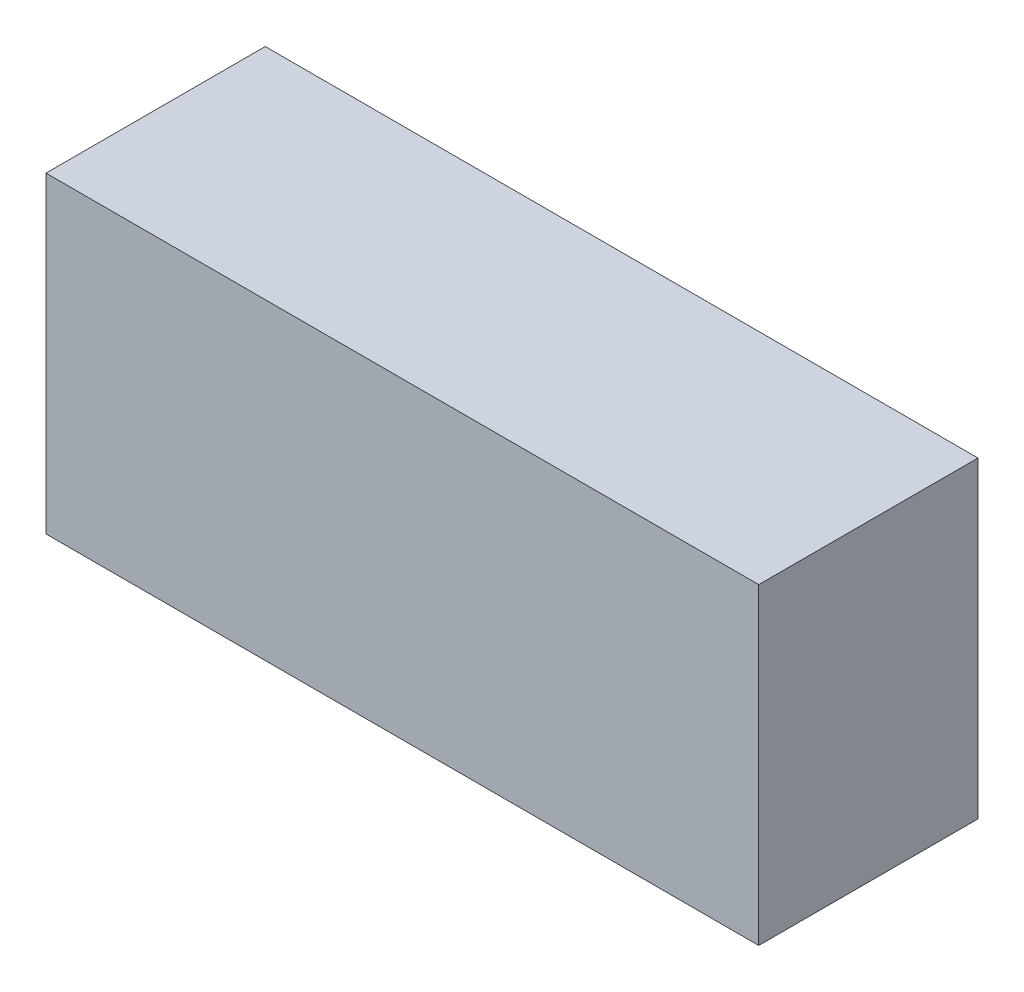
SolidWorks part; units mm, degrees
ref_plane "Front Plane" through (0, 0, 0) normal (0, 0, 1) x (1, 0, 0)
ref_plane "Top Plane" through (0, 0, 0) normal (0, 1, 0) x (1, 0, 0)
ref_plane "Right Plane" through (0, 0, 0) normal (1, 0, 0) x (0, 0, -1)
sketch "Sketch1" plane through (0, 0, 0) normal (0, 0, 1) x (1, 0, 0)
  line L0 (-1.6254, 0.7254) -> (1.6254, 0.7254)
  line L1 (1.6254, 0.7254) -> (1.6254, -0.7)
  line L2 (1.6254, -0.7) -> (-1.6254, -0.7)
  line L3 (-1.6254, -0.7) -> (-1.6254, 0.7254)
extrude "Component_Outline" add sketch "Sketch1" along normal blind 1 separate body
sketch3d "3DSketch1"
  line L0 (0, 0, 0) -> (1, 0, 0)
  line L1 (0, 0, 0) -> (0, 1, 0)
  line L2 (0, 0, 0) -> (0, 0, 1)
  point P0 (0, 0, 0)
